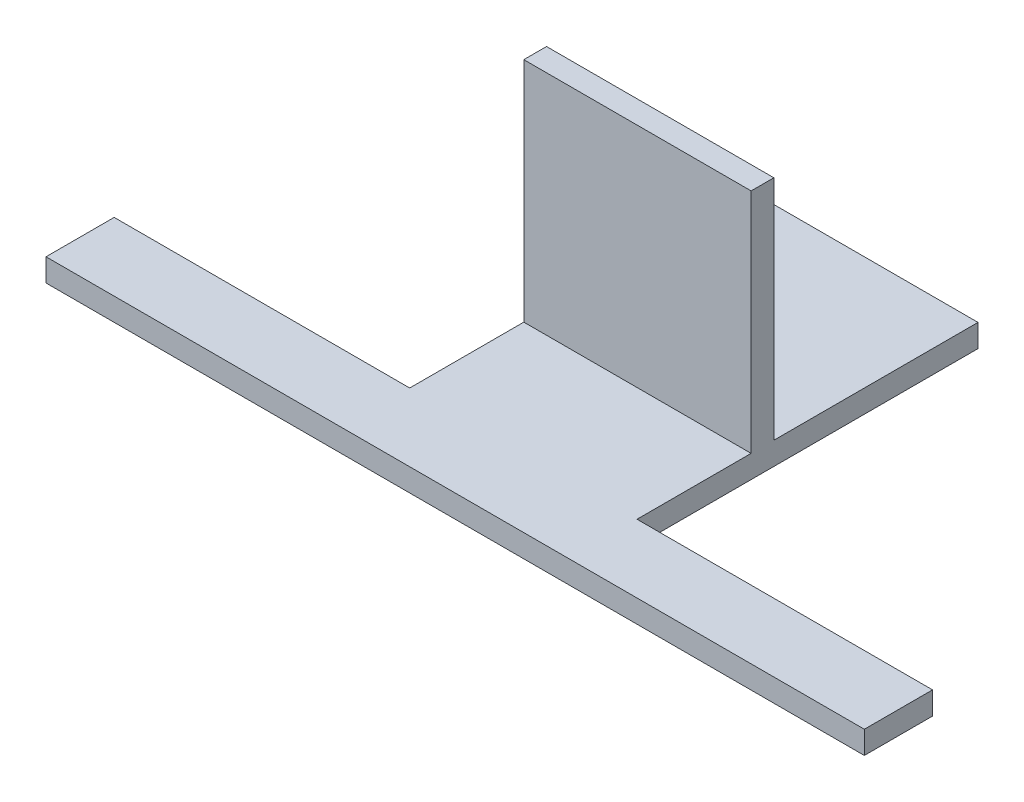
SolidWorks part; units mm, degrees
material "ABS"
ref_plane "Спереди" through (0, 0, 0) normal (0, 0, 1) x (1, 0, 0)
ref_plane "Сверху" through (0, 0, 0) normal (0, 1, 0) x (1, 0, 0)
ref_plane "Справа" through (0, 0, 0) normal (1, 0, 0) x (0, 0, -1)
sketch "Эскиз1" plane through (0, 0, 0) normal (0, 1, 0) x (1, 0, 0)
  line L1 (0, 0) -> (360, 0)
  line L2 (0, 0) -> (0, 30)
  line L3 (0, 30) -> (360, 30)
  line L4 (360, 0) -> (360, 30)
  dimension "D1" = 30
  dimension "D2" = 360
extrude "Бобышка-Вытянуть1" add sketch "Эскиз1" along normal blind 10
sketch "Эскиз2" plane through (0, 0, -30) normal (0, 0, -1) x (-1, 0, 0)
  line L0 (-180, 10) -> (-180, 0) construction
  line L1 (-360, 10) -> (0, 10) construction
  line L2 (-360, 0) -> (0, 0) construction
  line L4 (-230, 10) -> (-130, 10)
  line L5 (-230, 10) -> (-230, 0)
  line L6 (-230, 0) -> (-130, 0)
  line L7 (-130, 10) -> (-130, 0)
  dimension "D1" = 50
  dimension "D2" = 50
extrude "Бобышка-Вытянуть2" add sketch "Эскиз2" along normal blind 150
sketch "Эскиз3" plane through (0, 10, 0) normal (0, 1, 0) x (1, 0, 0)
  line L1 (130, 180) -> (130, 30) construction
  line L2 (130, 90.1928) -> (230, 90.1928)
  line L3 (130, 90.1928) -> (130, 80.1928)
  line L4 (130, 80.1928) -> (230, 80.1928)
  line L5 (230, 90.1928) -> (230, 80.1928)
  line L6 (230, 180) -> (230, 30) construction
  dimension "D1" = 10
extrude "Бобышка-Вытянуть3" add sketch "Эскиз3" along normal blind 100
